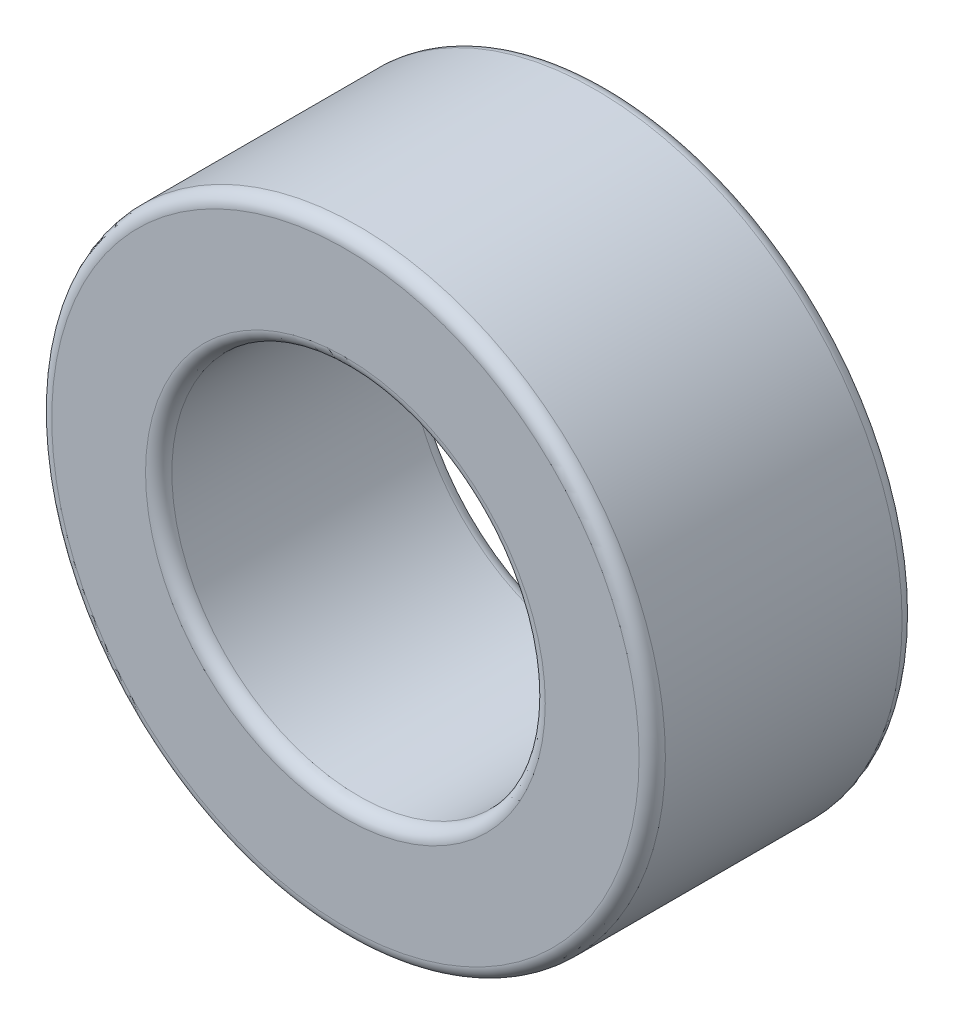
SolidWorks part; units mm, degrees
ref_plane "前视基准面" through (0, 0, 0) normal (0, 0, 1) x (1, 0, 0)
ref_plane "上视基准面" through (0, 0, 0) normal (0, 1, 0) x (1, 0, 0)
ref_plane "右视基准面" through (0, 0, 0) normal (1, 0, 0) x (0, 0, -1)
sketch "草图1" plane through (0, 0, 0) normal (0, 0, 1) x (1, 0, 0)
  circle A0 centre (0, 0) radius 3.5
  circle A1 centre (0, 0) radius 2.13
  dimension "D1" = 4.26
  dimension "D2" = 7
extrude "凸台-拉伸1" add sketch "草图1" along normal blind 3
fillet "圆角1" radius 0.15 4 edges at (2.13, 0, 0) (2.13, 0, 3) (3.5, 0, 0) (3.5, 0, 3)
